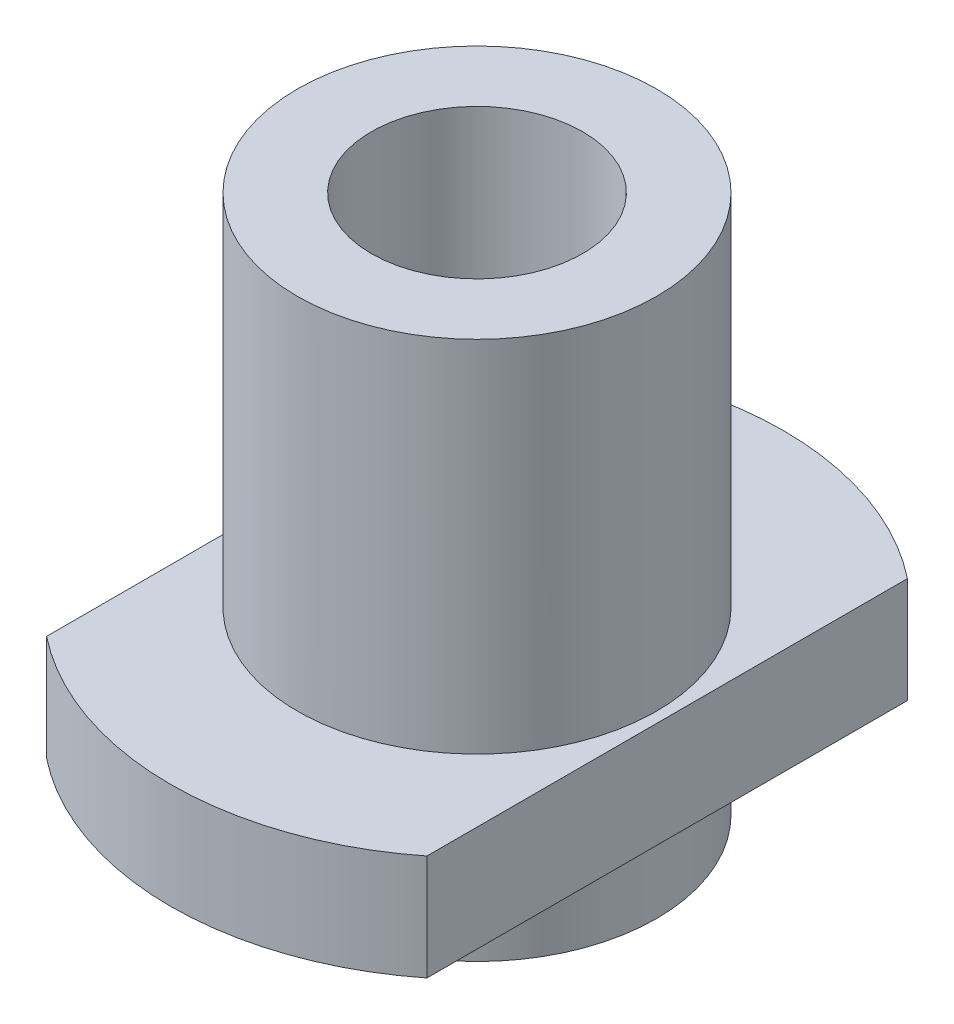
SolidWorks part; units mm, degrees
ref_plane "前视基准面" through (0, 0, 0) normal (0, 0, 1) x (1, 0, 0)
ref_plane "上视基准面" through (0, 0, 0) normal (0, 1, 0) x (1, 0, 0)
ref_plane "右视基准面" through (0, 0, 0) normal (1, 0, 0) x (0, 0, -1)
sketch "草图1" plane through (0, 0, 0) normal (0, 1, 0) x (1, 0, 0)
  circle A0 centre (0, 0) radius 17
  circle A1 centre (0, 0) radius 10
  dimension "D1" = 34
  dimension "D2" = 20
extrude "凸台-拉伸1" add sketch "草图1" along normal blind 51
sketch "草图7" plane through (0, 0, 0) normal (0, -1, 0) x (1, 0, 0)
  line L0 (-18, 22.7376) -> (-18, -22.7376)
  line L1 (18, 22.7376) -> (18, -22.7376)
  arc A0 (-18, -22.7376) -> (18, -22.7376) centre (0, 0) ccw
  arc A1 (18, 22.7376) -> (-18, 22.7376) centre (0, 0) ccw
  circle A2 centre (0, 0) radius 10
  dimension "D1" = 58
  dimension "D4" = 20
  dimension "D2" = 36
  dimension "D3" = 18
extrude "凸台-拉伸2" add sketch "草图7" against normal blind 10 from offset 7 offset against normal yes
